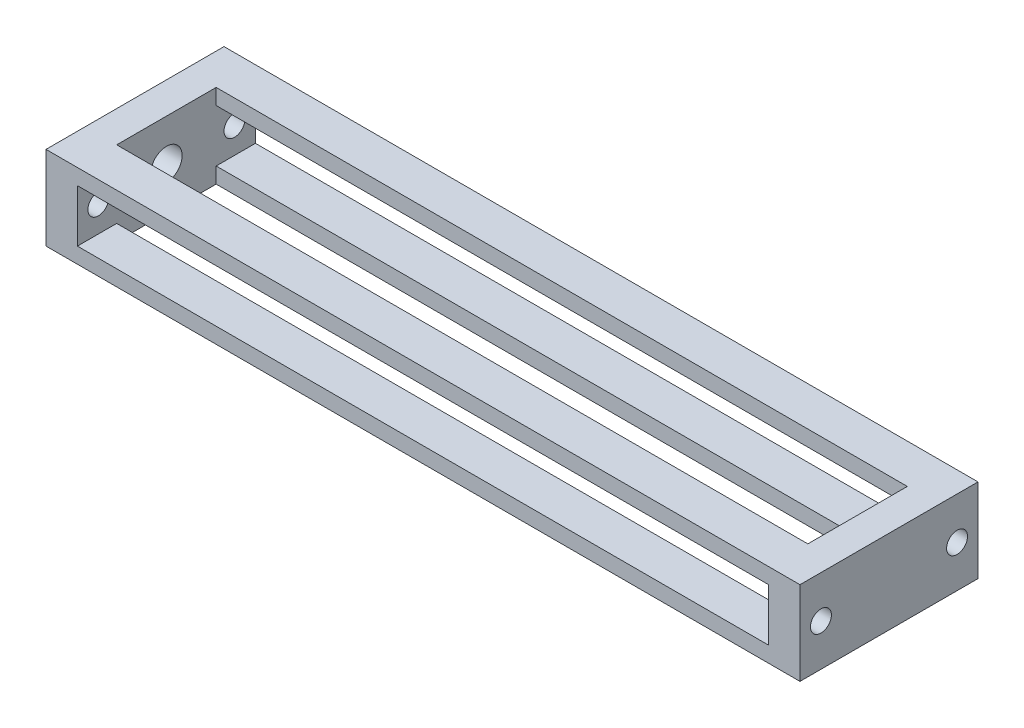
SolidWorks part; units mm, degrees
ref_plane "Front Plane" through (0, 0, 0) normal (0, 0, 1) x (1, 0, 0)
ref_plane "Top Plane" through (0, 0, 0) normal (0, 1, 0) x (1, 0, 0)
ref_plane "Right Plane" through (0, 0, 0) normal (1, 0, 0) x (0, 0, -1)
sketch "Sketch1" plane through (0, 0, 0) normal (0, 1, 0) x (1, 0, 0)
  line L5 (-457.2, 107.95) -> (457.2, 107.95)
  line L6 (-457.2, 107.95) -> (-457.2, -107.95)
  line L11 (-457.2, -107.95) -> (457.2, -107.95)
  line L12 (457.2, 107.95) -> (457.2, -107.95)
  line L17 (-457.2, 107.95) -> (457.2, -107.95) construction
  line L18 (-457.2, -107.95) -> (457.2, 107.95) construction
  line L23 (-450.85, 95.25) -> (450.85, 95.25) construction
  line L24 (-450.85, 95.25) -> (-450.85, 69.85) construction
  line L29 (-450.85, 69.85) -> (450.85, 69.85) construction
  line L30 (450.85, 95.25) -> (450.85, 69.85) construction
  line L31 (-450.85, 95.25) -> (450.85, 69.85) construction
  line L32 (-450.85, 69.85) -> (450.85, 95.25) construction
  line L33 (-450.85, -95.25) -> (450.85, -95.25) construction
  line L34 (-450.85, -95.25) -> (-450.85, -69.85) construction
  line L35 (-450.85, -69.85) -> (450.85, -69.85) construction
  line L36 (450.85, -95.25) -> (450.85, -69.85) construction
  line L37 (-450.85, -95.25) -> (450.85, -69.85) construction
  line L38 (-450.85, -69.85) -> (450.85, -95.25) construction
  line L39 (368.3, 57.15) -> (457.2, 57.15) construction
  line L40 (368.3, 57.15) -> (368.3, -57.15) construction
  line L41 (368.3, -57.15) -> (457.2, -57.15) construction
  line L42 (457.2, 57.15) -> (457.2, -57.15) construction
  line L43 (368.3, 57.15) -> (457.2, -57.15) construction
  line L44 (368.3, -57.15) -> (457.2, 57.15) construction
  point P0 (0, 0)
  point P5 (335.9456, 63.5)
  point P6 (0, 82.55)
  point P11 (0, -82.55)
  point P16 (865.448, -52.7166)
  point P17 (343.042, 4.05)
  point P18 (442.5453, 103.8183)
  point P19 (-745.2826, -73.8897)
  point P20 (412.75, 0)
  point P25 (-444.4198, -69.1357)
  point P26 (-217.1904, 0)
  point P27 (106.6141, 0)
  point P28 (369.4365, 0)
  point P30 (457.2, -63.5)
  point P31 (0, 0)
  point P32 (0, 0)
  point P33 (0, 0)
  dimension "D1" = 6.35
  dimension "D2" = 25.4
  dimension "D3" = 25.4
  dimension "D4" = 12.7
  dimension "D5" = 114.3
  dimension "D6" = 914.4
  dimension "D7" = 88.9
  dimension "D8" = 6.35
  dimension "D9" = 6.35
  dimension "D10" = 12.7
  dimension "D11" = 12.7
extrude "Boss-Extrude1" add sketch "Sketch1" along normal blind 101.6
sketch "Sketch2" plane through (0, 101.6, 0) normal (0, 1, 0) x (1, 0, 0)
  line L0 (457.2, -107.95) -> (457.2, 107.95) construction
  line L1 (-419.1, 60.325) -> (419.1, 60.325)
  line L2 (-419.1, 60.325) -> (-419.1, -60.325)
  line L3 (-419.1, -60.325) -> (419.1, -60.325)
  line L4 (419.1, 60.325) -> (419.1, -60.325)
  line L5 (-419.1, 60.325) -> (419.1, -60.325) construction
  line L6 (-419.1, -60.325) -> (419.1, 60.325) construction
  point P0 (0, 0)
  dimension "D1" = 38.1
  dimension "D2" = 120.65
extrude "Cut-Extrude1" cut sketch "Sketch2" against normal up to next
sketch "Sketch3" plane through (0, 0, 107.95) normal (0, 0, 1) x (1, 0, 0)
  line L0 (-457.2, 101.6) -> (457.2, 101.6) construction
  line L1 (-419.1, 82.55) -> (419.1, 82.55)
  line L2 (-419.1, 82.55) -> (-419.1, 19.05)
  line L3 (-419.1, 19.05) -> (419.1, 19.05)
  line L4 (419.1, 82.55) -> (419.1, 19.05)
  line L5 (-419.1, 82.55) -> (419.1, 19.05) construction
  line L6 (-419.1, 19.05) -> (419.1, 82.55) construction
  line L7 (-457.2, 0) -> (457.2, 0) construction
  line L8 (457.2, 101.6) -> (457.2, 0) construction
  line L9 (-457.2, 101.6) -> (-457.2, 0) construction
  point P0 (0, 50.8)
  dimension "D1" = 19.05
  dimension "D2" = 19.05
  dimension "D3" = 38.1
  dimension "D4" = 38.1
extrude "Cut-Extrude2" cut sketch "Sketch3" against normal through all both and the other way through all
sketch "Sketch4" plane through (-457.2, 0, 0) normal (-1, 0, 0) x (0, 0, 1)
  line L0 (107.95, 101.6) -> (107.95, 0) construction
  line L1 (-107.95, 101.6) -> (-107.95, 0) construction
  circle A0 centre (82.55, 50.8) radius 12.7
  circle A1 centre (-82.55, 50.8) radius 12.7
  point P8 (88.9, 49.6918)
  point P9 (107.95, 50.8)
  dimension "D1" = 25.4
  dimension "D2" = 25.4
  dimension "D3" = 25.4
extrude "Cut-Extrude3" cut sketch "Sketch4" against normal through all both
sketch "Sketch5" plane through (-457.2, 0, 0) normal (-1, 0, 0) x (0, 0, 1)
  line L0 (-107.95, 0) -> (107.95, 0) construction
  line L1 (107.95, 101.6) -> (107.95, 0) construction
  circle A0 centre (0, 50.8) radius 19.05
  point P4 (0, 0)
  point P7 (0, 0)
  point P8 (107.95, 50.8)
  dimension "D1" = 38.1
extrude "Cut-Extrude4" cut sketch "Sketch5" against normal up to next
